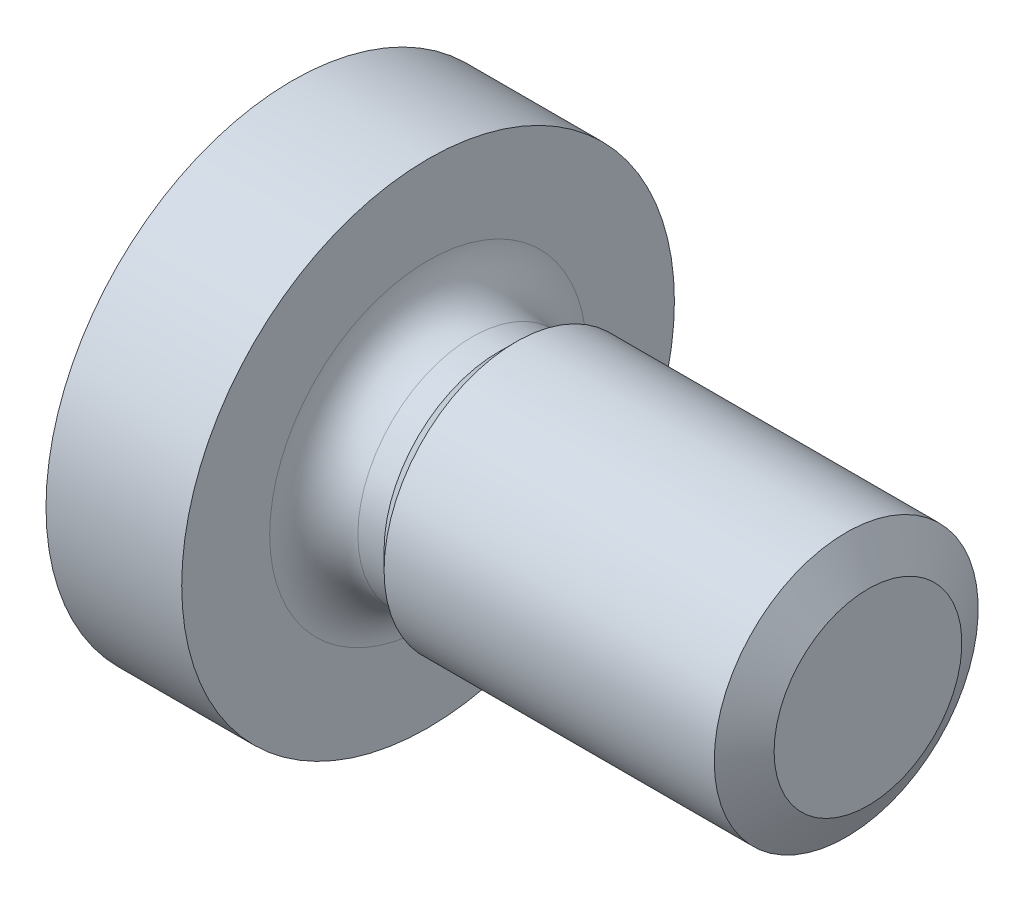
SolidWorks part; units mm, degrees
revolve "基体-旋转" add sketch "草图2" angle 360 about L0
sketch "草图2" plane through (0, 0, 0) normal (0, 0, 1) x (1, 0, 0)
  line L0 (-1.3318, 0) -> (6.5885, 0) construction
  line L1 (0, 0) -> (7.4, 0)
  line L2 (7.4, 0) -> (7.4, 1.5)
  line L3 (7.4, 1.5) -> (3.4, 1.5)
  line L4 (3.4, 1.5) -> (3.199, 1.299)
  line L5 (3.199, 1.299) -> (2.901, 1.299)
  line L6 (2.4, 1.8) -> (2.4, 2.8)
  line L7 (2.4, 2.8) -> (0.8575, 2.8)
  arc A0 (2.4, 1.8) -> (2.901, 1.299) centre (2.901, 1.8) ccw
  arc A1 (0, 0) -> (0.8575, 2.8) centre (5, 0) cw
  dimension "D3" = 5
  dimension "dk" = 5.6
  dimension "d" = 3
  dimension "l" = 5
  dimension "a" = 1
  dimension "D1" = 45
  dimension "D2" = 2.598
  dimension "da" = 3.6
  dimension "k" = 2.4
cosmetic thread "装饰螺纹线1" parameters "D1"=4, "D2"=2.598
material "AISI 304"
ref_plane "前视" through (0, 0, 0) normal (0, 0, 1) x (1, 0, 0)
ref_plane "上视" through (0, 0, 0) normal (0, 1, 0) x (1, 0, 0)
ref_plane "右视" through (0, 0, 0) normal (1, 0, 0) x (0, 0, -1)
sketch "尺寸草图" plane through (0, 0, 0) normal (0, 0, 1) x (1, 0, 0)
  line L0 (0, 0) -> (5, 0)
  line L1 (0, 0) -> (0, 5.6)
  line L2 (5, 0) -> (5, 3.6)
  point P5 (0, 3)
  point P6 (4.5, 0)
  point P7 (1, 0)
  point P8 (2.4, 0)
  point P9 (0, 0)
  point P10 (3, 0)
  point P11 (3.2, 0)
  dimension "dk" = 5.6
  dimension "d" = 3
  dimension "l" = 5
  dimension "a" = 1
  dimension "da" = 3.6
  dimension "k" = 2.4
  dimension "P" = 0.5
  dimension "rf" = 5
  dimension "m" = 3
  dimension "h" = 1.8
sketch "草图3" plane through (0, 0, 0) normal (0, 0, 1) x (1, 0, 0)
  line L0 (7.1527, 1.5) -> (7.6527, 1.5)
  line L1 (7.6527, 1.5) -> (7.4, 1.067)
  line L2 (7.4, 1.067) -> (7.1527, 1.5)
  line L3 (7.4, 1.5) -> (3.4, 1.5) construction
  line L4 (7.4, -1.5) -> (7.4, 1.5) construction
  line L5 (-0.2428, 0) -> (7.1644, 0) construction
  line L6 (-1.3318, 0) -> (6.5885, 0) construction
  dimension "P" = 0.5
  dimension "D1" = 0.433
  dimension "D2" = 60
revolve "切除-旋转1" cut sketch "草图3" angle 360 about L5
sketch "草图5" plane through (0, 0, 0) normal (1, 0, 0) x (0, 0, -1)
  line L1 (0.25, 1.5) -> (-0.25, 1.5)
  line L2 (0.25, 1.5) -> (0.25, -1.5)
  line L3 (0.25, -1.5) -> (-0.25, -1.5)
  line L4 (-0.25, 1.5) -> (-0.25, -1.5)
  point P4 (0.25, 0)
  point P5 (0, 1.5)
  dimension "m" = 3
  dimension "D1" = 0.5
ref_plane "基准面1" through (1.8, 0, 0) normal (1, 0, 0) x (0, 0, -1)
pattern_linear "阵列(线性)1" [suppressed] count 9 spacing 0.5 along (1, 0, 0)
sketch "草图6" plane through (1.8, 0, 0) normal (1, 0, 0) x (0, 0, -1)
  point P0 (0, 0)
loft "切除-放样1" cut profiles "草图6", "草图5"
ref_plane "基准面2" through (0, 0, 0) normal (0, -0.7071, 0.7071) x (1, 0, 0)
mirror "镜向1" about plane through (0, 0, 0) normal (0, -0.7071, 0.7071) of "切除-放样1"
equation "\"l@草图2\" = \"l@尺寸草图\""
equation "\"dk@草图2\" = \"dk@尺寸草图\""
equation "\"k@草图2\" = \"k@尺寸草图\""
equation "\"D2@草图2\" = \"d@尺寸草图\"*0.866"
equation "\"a@草图2\" = \"a@尺寸草图\""
equation "\"D3@草图2\" = \"rf@尺寸草图\""
equation "\"d@草图2\" = \"d@尺寸草图\""
equation "\"da@草图2\" = \"da@尺寸草图\""
equation "\"D2@装饰螺纹线1\" = \"d@尺寸草图\"*0.866"
equation "\"D1@装饰螺纹线1\" = \"l@尺寸草图\"-\"a@尺寸草图\""
equation "\"P@草图3\" = \"P@尺寸草图\""
equation "\"D1@草图3\" = \"P@尺寸草图\"*0.866"
equation "\"h@基准面1\" = \"h@尺寸草图\""
equation "\"D1@草图5\" = \"P@尺寸草图\""
equation "\"m@草图5\" = \"m@尺寸草图\""
equation "\"D3@阵列(线性)1\" = \"P@尺寸草图\""
equation "\"D1@阵列(线性)1\" = (\"l@尺寸草图\"-\"a@尺寸草图\")/\"P@尺寸草图\"+1"
